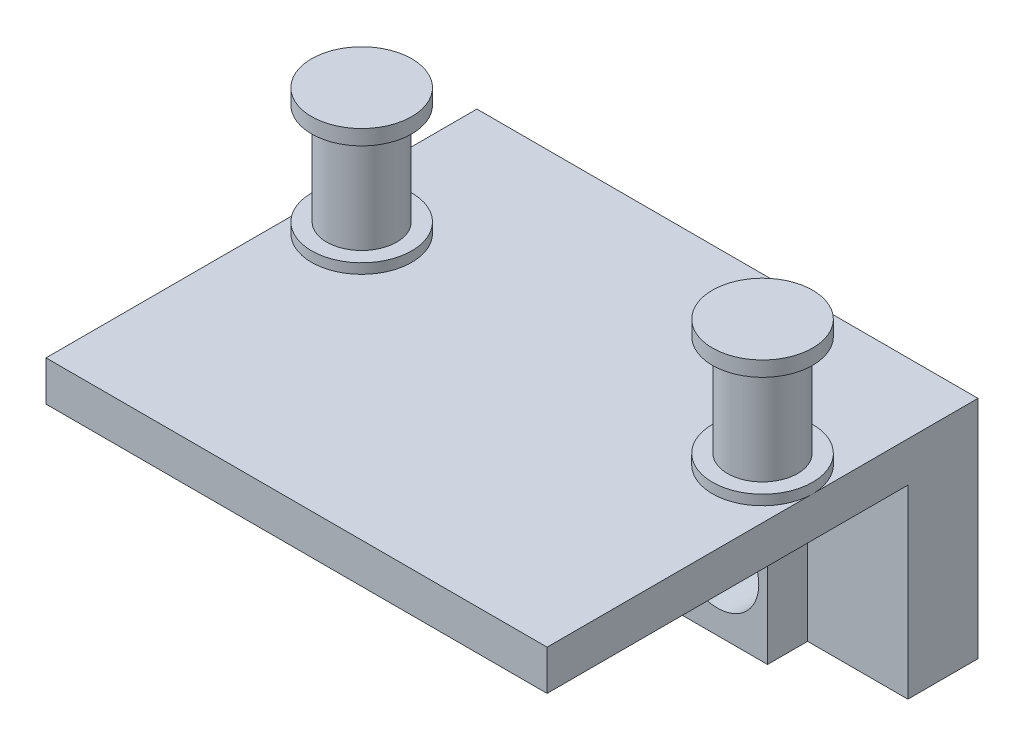
SolidWorks part; units mm, degrees
ref_plane "Front Plane" through (0, 0, 0) normal (0, 0, 1) x (1, 0, 0)
ref_plane "Top Plane" through (0, 0, 0) normal (0, 1, 0) x (1, 0, 0)
ref_plane "Right Plane" through (0, 0, 0) normal (1, 0, 0) x (0, 0, -1)
sketch "Sketch1" plane through (0, 0, 0) normal (1, 0, 0) x (0, 0, -1)
  line L0 (16.6989, -1.875) -> (-15.3011, -1.875)
  line L1 (-15.3011, -1.875) -> (-15.3011, -5.875)
  line L12 (-15.3011, -5.875) -> (-6.3011, -5.875)
  line L13 (-6.3011, -5.875) -> (-5.3011, -6.675)
  line L14 (-5.3011, -6.675) -> (6.1989, -6.675)
  line L15 (6.1989, -6.675) -> (7.1989, -5.875)
  line L16 (7.1989, -5.875) -> (16.1989, -5.875)
  line L17 (16.1989, -5.875) -> (17.6989, -6.875)
  line L18 (17.6989, -6.875) -> (17.6989, -12.375)
  line L19 (17.6989, -12.375) -> (16.6989, -13.375)
  line L20 (16.6989, -13.375) -> (16.6989, -24.375)
  line L21 (16.6989, -24.375) -> (20.6989, -24.375)
  line L22 (20.6989, -24.375) -> (20.6989, -1.875)
  line L23 (20.6989, -1.875) -> (16.6989, -1.875)
  dimension "D1" = 9
  dimension "D2" = 9
  dimension "D3" = 11.5
  dimension "D4" = 0.8
  dimension "D5" = 0.8
  dimension "D6" = 1
  dimension "D7" = 1
  dimension "D8" = 1.5
  dimension "D9" = 1
  dimension "D10" = 5.5
  dimension "D11" = 1
  dimension "D12" = 4
  dimension "D13" = 11
extrude "Boss-Extrude1" add sketch "Sketch1" along normal blind 30 contours L0 L1 L12 L13 L14 L15 L16 L17 L18 L19 L20 L21 L22 L23
sketch "Sketch2" plane through (0, 0, -20.6989) normal (0, 0, -1) x (-1, 0, 0)
  line L0 (-30, -13.375) -> (0, -13.375) construction
  line L1 (0, -13.375) -> (-30, -24.375) construction
  line L2 (-30, -24.375) -> (0, -24.375) construction
  line L3 (0, -24.375) -> (-30, -13.375) construction
  line L4 (-30, -17.875) -> (0, -17.875) construction
  line L5 (-30, -24.375) -> (-30, -1.875) construction
  line L6 (0, -24.375) -> (0, -1.875) construction
  line L7 (-15, -18.875) -> (-15, -13.375) construction
  circle A0 centre (-25, -17.875) radius 4.125
  circle A1 centre (-5, -17.875) radius 4.125
  dimension "D1" = 8.25
  dimension "D2" = 10
extrude "Cut-Extrude1" cut sketch "Sketch2" against normal through all
sketch "Sketch3" plane through (0, 0, 0) normal (-1, 0, 0) x (0, 0, 1)
  line L0 (-20.6989, -24.375) -> (-20.6989, -1.875) construction
  line L1 (15.3011, -1.875) -> (-20.6989, -1.875)
  line L2 (15.3011, -1.875) -> (15.3011, -5.8728)
  line L3 (15.3011, -5.8728) -> (-20.6989, -5.8728)
  line L4 (-20.6989, -1.875) -> (-20.6989, -5.8728)
extrude "Boss-Extrude2" add sketch "Sketch3" along normal blind 10
sketch "Sketch4" plane through (30, 0, 0) normal (1, 0, 0) x (0, 0, -1)
  line L1 (-15.3011, -5.875) -> (20.6989, -5.875)
  line L2 (-15.3011, -5.875) -> (-15.3011, -1.875)
  line L3 (-15.3011, -1.875) -> (20.6989, -1.875)
  line L4 (20.6989, -5.875) -> (20.6989, -1.875)
extrude "Boss-Extrude3" add sketch "Sketch4" along normal blind 10
sketch "Sketch5" plane through (0, -1.875, 0) normal (0, 1, 0) x (1, 0, 0)
  line L0 (-10, 2.6989) -> (40, 2.6989) construction
  line L1 (-10, -15.3011) -> (-10, 20.6989) construction
  line L2 (40, 20.6989) -> (40, -15.3011) construction
  line L3 (15, 20.6989) -> (15, -15.3011) construction
  line L4 (40, 20.6989) -> (-10, 20.6989) construction
  line L5 (40, -15.3011) -> (-10, -15.3011) construction
  circle A0 centre (35, 11.1989) radius 5
  circle A1 centre (-5, 11.1989) radius 5
  dimension "D1" = 10
  dimension "D2" = 8.5
  dimension "D3" = 5
extrude "Boss-Extrude4" add sketch "Sketch5" along normal blind 12.6 contours A1 | A0
sketch "Sketch6" plane through (0, 0, -20.6989) normal (0, 0, -1) x (-1, 0, 0)
  line L1 (-30, -24.375) -> (0, -24.375)
  line L2 (-30, -24.375) -> (-30, -1.875)
  line L3 (-30, -1.875) -> (0, -1.875)
  line L4 (0, -24.375) -> (0, -1.875)
  circle A0 centre (-25, -17.875) radius 4.125
  circle A2 centre (-5, -17.875) radius 4.125
  circle A3 centre (-25, -17.875) radius 4.125 construction
  circle A4 centre (-5, -17.875) radius 4.125 construction
extrude "Boss-Extrude5" add sketch "Sketch6" along normal blind 7
ref_plane "Plane1" through (0, -0.875, 0) normal (0, 1, 0) x (1, 0, 0)
sketch "Sketch8" plane through (0, -0.875, 0) normal (0, 1, 0) x (1, 0, 0)
  circle A0 centre (-5, 11.1989) radius 5
  circle A1 centre (-5, 11.1989) radius 3.5
  circle A2 centre (35, 11.1989) radius 5
  circle A3 centre (35, 11.1989) radius 3.5
  dimension "D1" = 7
  dimension "D2" = 7
extrude "Cut-Extrude2" cut sketch "Sketch8" along normal offset from surface (10.1 mm away) 1.5 up to face at (35, 10.725, -6.1989)
sketch "Sketch9" plane through (30, 0, 0) normal (1, 0, 0) x (0, 0, -1)
  line L0 (16.6989, -24.375) -> (27.6989, -24.375) construction
  line L1 (27.6989, -1.875) -> (20.6989, -1.875)
  line L2 (27.6989, -1.875) -> (27.6989, -24.375)
  line L3 (27.6989, -24.375) -> (20.6989, -24.375)
  line L4 (20.6989, -1.875) -> (20.6989, -24.375)
extrude "Boss-Extrude6" add sketch "Sketch9" along normal up to surface (10 mm away) up to face at (40, -3.475, -4.3989)
sketch "Sketch10" plane through (0, 0, 0) normal (-1, 0, 0) x (0, 0, 1)
  line L1 (-20.6989, -1.875) -> (-27.6989, -1.875)
  line L2 (-20.6989, -1.875) -> (-20.6989, -24.375)
  line L3 (-20.6989, -24.375) -> (-27.6989, -24.375)
  line L4 (-27.6989, -1.875) -> (-27.6989, -24.375)
extrude "Boss-Extrude7" add sketch "Sketch10" along normal up to surface (10 mm away) up to face at (-10, -3.4741, -4.3989)
